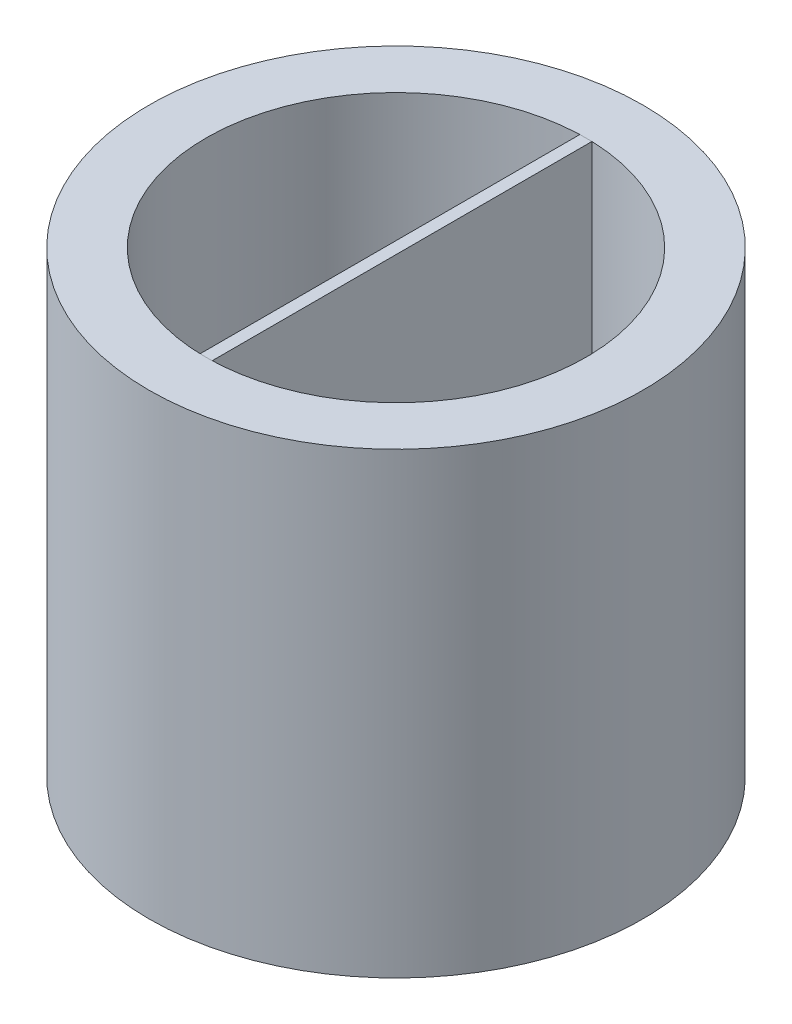
SolidWorks part; units mm, degrees
ref_plane "Front Plane" through (0, 0, 0) normal (0, 0, 1) x (1, 0, 0)
ref_plane "Top Plane" through (0, 0, 0) normal (0, 1, 0) x (1, 0, 0)
ref_plane "Right Plane" through (0, 0, 0) normal (1, 0, 0) x (0, 0, -1)
sketch "Sketch1" plane through (0, 0, 0) normal (0, 1, 0) x (1, 0, 0)
  circle A0 centre (0, 0) radius 130
extrude "Boss-Extrude1" add sketch "Sketch1" along normal blind 241.01
sketch "Sketch2" plane through (0, 241.01, 0) normal (0, 1, 0) x (1, 0, 0)
  circle A0 centre (0, 0) radius 100
extrude "Cut-Extrude1" cut sketch "Sketch2" against normal through all
sketch "Sketch3" plane through (0, 241.01, 0) normal (0, 1, 0) x (1, 0, 0)
  line L0 (0, 0) -> (0, 130) construction
  line L1 (0, 0) -> (0, -128.9732) construction
  line L2 (0, 0) -> (3.175, 0) construction
  line L3 (0, 0) -> (-3.175, 0) construction
  line L4 (3.175, 0) -> (3.175, 99.9496) construction
  line L5 (3.175, 0) -> (3.175, -99.9496) construction
  line L6 (-3.175, 0) -> (-3.175, 99.9496) construction
  line L7 (-3.175, 0) -> (-3.175, -99.9496) construction
  circle A0 centre (0, 0) radius 130 construction
  circle A1 centre (0, 0) radius 100 construction
  arc A2 (-3.175, 99.9496) -> (0, 100) centre (0, 0) ccw
  arc A3 (-3.175, -99.9496) -> (0, -100) centre (0, 0) cw
  arc A4 (0, -100) -> (1.3909, -99.9903) centre (0, 0) cw
sketch "Sketch5" plane through (0, 0, 0) normal (0, 1, 0) x (1, 0, 0)
  line L0 (-3.175, 99.9496) -> (-3.175, -99.9496)
  line L1 (3.175, -99.9496) -> (3.175, 99.9496)
  line L2 (-3.175, 99.9496) -> (3.175, 99.9496)
  line L3 (-3.175, -99.9496) -> (3.175, -99.9496)
extrude "Boss-Extrude2" add sketch "Sketch5" along normal blind 241.01 separate body
